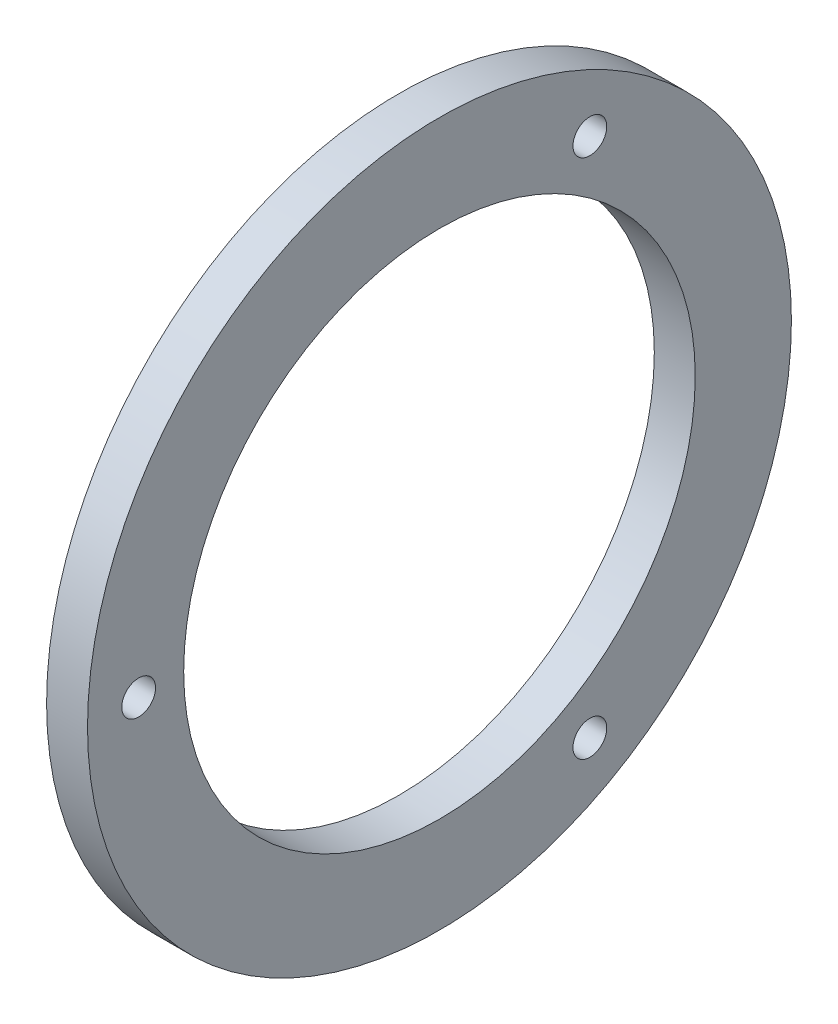
SolidWorks part; units mm, degrees
ref_plane "Front Plane" through (0, 0, 0) normal (0, 0, 1) x (1, 0, 0)
ref_plane "Top Plane" through (0, 0, 0) normal (0, 1, 0) x (1, 0, 0)
ref_plane "Right Plane" through (0, 0, 0) normal (1, 0, 0) x (0, 0, -1)
sketch "Axial profile (mm)" plane through (0, 0, 0) normal (0, 0, 1) x (1, 0, 0)
  line L0 (-110, 0) -> (75, 0) construction
  line L1 (159.7, 25) -> (163.7, 25)
  line L2 (163.7, 25) -> (163.7, 34.4)
  line L3 (163.7, 34.4) -> (159.7, 34.4)
  line L4 (159.7, 34.4) -> (159.7, 25)
revolve "Full revolution" add sketch "Axial profile (mm)" angle 360 about L0
sketch "Sketch2" plane through (0, 0, 0) normal (1, 0, 0) x (0, 0, -1)
  circle A0 centre (-29.4, 0) radius 1.65
  circle A1 centre (14.7, -25.4611) radius 1.65
  circle A2 centre (14.7, 25.4611) radius 1.65
extrude "Axial holes" cut sketch "Sketch2" against normal through all and the other way through all
